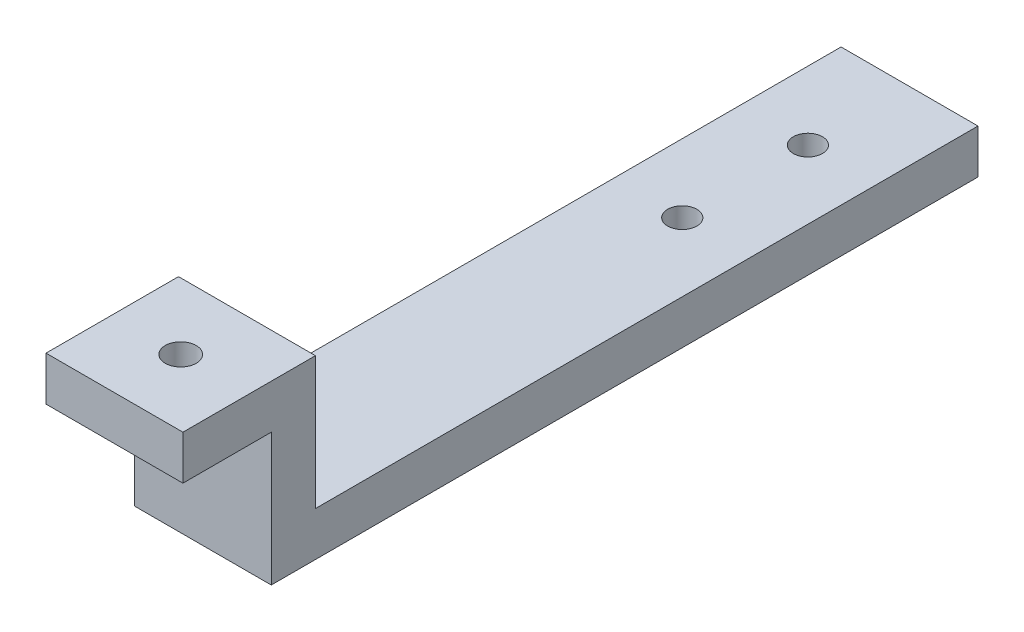
SolidWorks part; units mm, degrees
material "Galvanized Steel"
ref_plane "Front Plane" through (0, 0, 0) normal (0, 0, 1) x (1, 0, 0)
ref_plane "Top Plane" through (0, 0, 0) normal (0, 1, 0) x (1, 0, 0)
ref_plane "Right Plane" through (0, 0, 0) normal (1, 0, 0) x (0, 0, -1)
sketch "Sketch1" plane through (0, 0, 0) normal (1, 0, 0) x (0, 0, -1)
  line L0 (0, 0) -> (30, 0)
  line L1 (30, 0) -> (30, -29.972)
  line L2 (30, -29.972) -> (180, -29.972)
  dimension "D1" = 30
  dimension "D2" = 29.972
extrude "Extrude-Thin1" add sketch "Sketch1" along normal blind 31 thin contours L0 L1 L2
sketch "Sketch6" plane through (0, 0, 0) normal (0, 1, 0) x (1, 0, 0)
  line L0 (0, 0) -> (0, 30) construction
  line L2 (31, 30) -> (0, 30) construction
  circle A0 centre (15.5, 15) radius 3.5
  dimension "D1" = 7
  dimension "D2" = 15.5
  dimension "D3" = 15
extrude "Cut-Extrude1" cut sketch "Sketch6" against normal blind 10
sketch "Sketch7" plane through (0, -29.972, 0) normal (0, 1, 0) x (1, 0, 0)
  line L0 (31, 30) -> (0, 30) construction
  line L2 (0, 30) -> (0, 180) construction
  circle A0 centre (15.494, 157) radius 3.302
  dimension "D1" = 6.604
  dimension "D3" = 15.494
  dimension "D2" = 127
extrude "Cut-Extrude3" cut sketch "Sketch7" against normal blind 10.16
hole_wizard "#97 (0.26) Diameter Hole1" positions "Sketch10" profile "Sketch11" hole size "#97" standard "ANSI Inch"
sketch "Sketch10" plane through (0, -29.972, 0) normal (0, 1, 0) x (1, 0, 0)
  point P0 (15.494, 128.552)
  point P4 (0, 0)
  dimension "D1" = 28.448
sketch "Sketch11" plane through (15.494, -29.972, -128.552) normal (1, 0, 0) x (0, 0, 1)
  line L0 (0, 0) -> (0, 27.384)
  line L1 (0, 27.384) -> (3.302, 25.4)
  line L2 (3.302, 25.4) -> (3.302, 0)
  line L5 (3.302, 0) -> (0, 0)
  line L10 (0, 27.384) -> (-3.302, 25.4) construction
  line L11 (0, -6.35) -> (0, 107.95) construction
  dimension "Hole Dia." = 6.604
  dimension "Hole Depth" = 25.4
  dimension "Drill Angle" = 118
